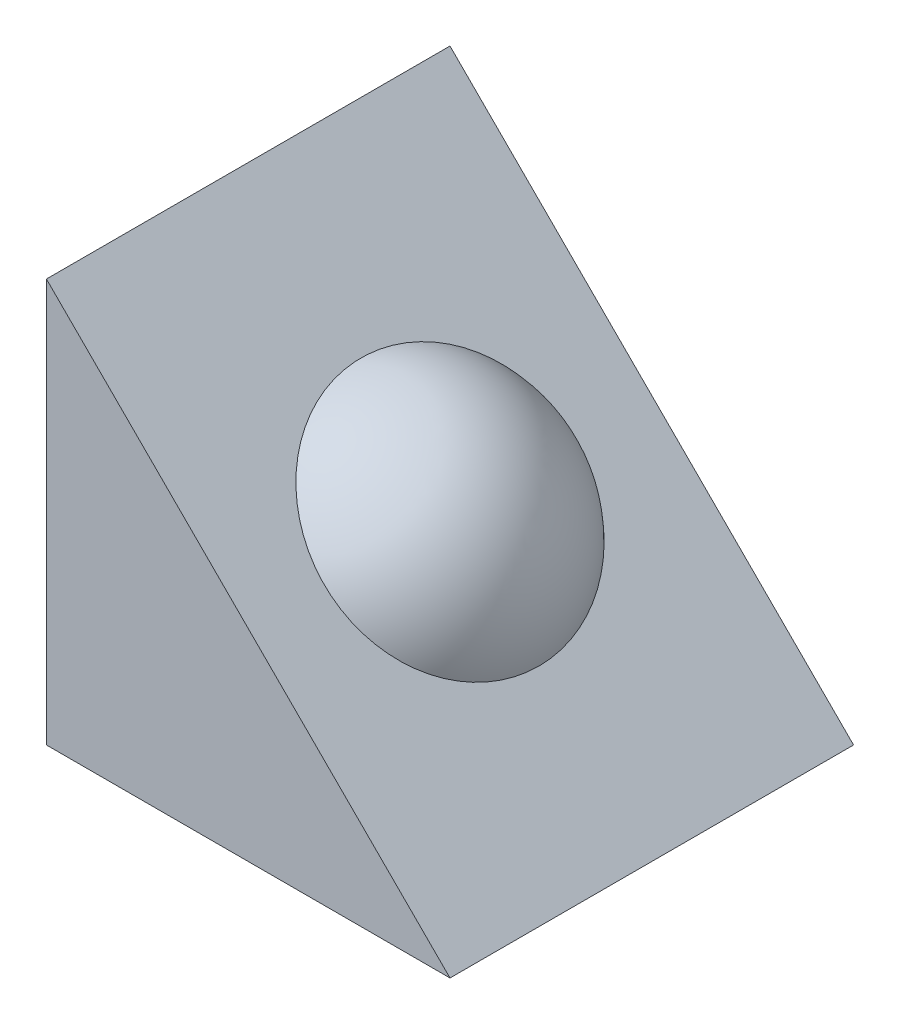
SolidWorks part; units mm, degrees
ref_plane "Front Plane" through (0, 0, 0) normal (0, 0, 1) x (1, 0, 0)
ref_plane "Top Plane" through (0, 0, 0) normal (0, 1, 0) x (1, 0, 0)
ref_plane "Right Plane" through (0, 0, 0) normal (1, 0, 0) x (0, 0, -1)
sketch "Sketch1" plane through (0, 0, 0) normal (0, 0, 1) x (1, 0, 0)
  line L0 (0, 50) -> (0, 0)
  line L1 (0, 0) -> (50, 0)
  line L2 (50, 0) -> (0, 50)
  dimension "D1" = 50
  dimension "D2" = 50
extrude "Boss-Extrude1" add sketch "Sketch1" along normal mid plane 50
sketch "Sketch2" plane through (0, 0, 0) normal (0, 0, 1) x (1, 0, 0)
  line L0 (0, 0) -> (25, 25) construction
  line L1 (50, 0) -> (0, 50) construction
  line L2 (5.9081, 31.364) -> (31.364, 5.9081)
  arc A0 (5.9081, 31.364) -> (31.364, 5.9081) centre (18.636, 18.636) cw
  point P8 (18.636, 18.636)
  dimension "D3" = 18
  dimension "D1" = 36
  dimension "D2" = 9
revolve "Revolve1" add sketch "Sketch2" angle 360 about L2
